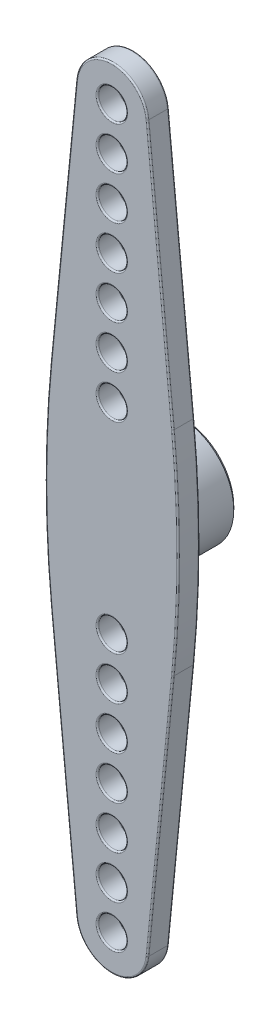
SolidWorks part; units mm, degrees
ref_plane "Front Plane" through (0, 0, 0) normal (0, 0, 1) x (1, 0, 0)
ref_plane "Top Plane" through (0, 0, 0) normal (0, 1, 0) x (1, 0, 0)
ref_plane "Right Plane" through (0, 0, 0) normal (1, 0, 0) x (0, 0, -1)
sketch "Sketch1" plane through (0, 0, 0) normal (0, 0, 1) x (1, 0, 0)
  line L0 (0, -25) -> (0, 25) construction
  line L1 (-2.5, -25) -> (-2.5, 25) construction
  line L2 (2.5, -25) -> (2.5, 25) construction
  line L3 (-5, 0) -> (5, 0) construction
  line L4 (-5, 0) -> (-2.4877, 25.2475)
  line L5 (2.4877, 25.2475) -> (5, 0)
  line L6 (2.4877, -25.2475) -> (5, 0)
  line L7 (-5, 0) -> (-2.4877, -25.2475)
  arc A0 (-2.5, -25) -> (2.5, -25) centre (0, -25) ccw construction
  arc A1 (2.5, 25) -> (-2.5, 25) centre (0, 25) ccw construction
  arc A2 (-2.4877, 25.2475) -> (2.4877, 25.2475) centre (0, 25) cw
  circle A3 centre (0, 25) radius 1
  circle A4 centre (0, 22) radius 1
  circle A5 centre (0, 19) radius 1
  circle A6 centre (0, 16) radius 1
  circle A7 centre (0, 13) radius 1
  circle A8 centre (0, 10) radius 1
  circle A9 centre (0, 7) radius 1
  circle A10 centre (0, -7) radius 1
  circle A11 centre (0, -10) radius 1
  circle A12 centre (0, -13) radius 1
  circle A13 centre (0, -16) radius 1
  circle A14 centre (0, -19) radius 1
  circle A15 centre (0, -22) radius 1
  circle A16 centre (0, -25) radius 1
  arc A17 (-2.4877, -25.2475) -> (2.4877, -25.2475) centre (0, -25) ccw
  point P2 (0, 0)
  dimension "D4" = 2
  dimension "D1" = 5
  dimension "D2" = 25
  dimension "D3" = 10
  dimension "D6" = 3
  dimension "D5" = 7
extrude "Boss-Extrude1" add sketch "Sketch1" along normal blind 1.5
fillet "Fillet1" radius 75 2 edges at (-5, 0, 0.75) (5, 0, 0.75)
sketch "Sketch2" plane through (0, 0, 0) normal (0, 0, -1) x (-1, 0, 0)
  circle A0 centre (0, 0) radius 1
  dimension "D1" = 2
extrude "Extrude-Thin1" add sketch "Sketch2" along normal blind 3.5 thin
chamfer "Chamfer1" distance 0.25 angle 45 2 edges at (-1, 0, -3.5) (-3.75, 0, -3.5)
fillet "Fillet2" radius 0.1 45 edges at (-1, -25, 1.5) (-1, -19, 1.5) (-1, -13, 1.5) (-1, -7, 1.5) (1, 10, 1.5) (1, 16, 1.5) (1, 22, 1.5) (0, 27.5, 1.5) (3.3744, 16.3369, 1.5) (4.6296, 0, 1.5) (3.3744, -16.3369, 1.5) (0, -27.5, 1.5) (-3.3744, -16.3369, 1.5) (-4.6296, 0, 1.5) (-3.3744, 16.3369, 1.5) (1, 25, 1.5) (1, 19, 1.5) (1, 13, 1.5) (1, 7, 1.5) (-1, -10, 1.5) (-1, -16, 1.5) (-1, -22, 1.5) (-1, -25, 0) (-1, -22, 0) (-1, -19, 0) (-1, -16, 0) (-1, -13, 0) (-1, -10, 0) (-1, -7, 0) (1, 7, 0) (1, 10, 0) (1, 13, 0) (1, 16, 0) (1, 19, 0) (1, 22, 0) (1, 25, 0) (0, -27.5, 0) (3.3744, -16.3369, 0) (4.6296, 0, 0) (3.3744, 16.3369, 0) (0, 27.5, 0) (-3.3744, 16.3369, 0) (-4.6296, 0, 0) (-3.3744, -16.3369, 0) (3.75, 0, 0)
